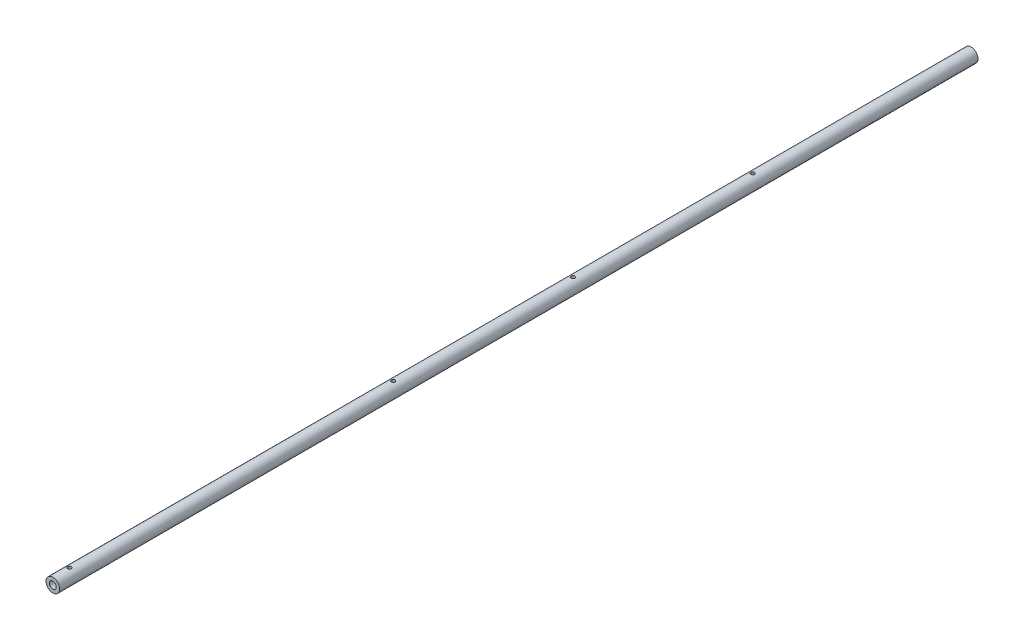
SolidWorks part; units mm, degrees
ref_plane "Front Plane" through (0, 0, 0) normal (0, 0, 1) x (1, 0, 0)
ref_plane "Top Plane" through (0, 0, 0) normal (0, 1, 0) x (1, 0, 0)
ref_plane "Right Plane" through (0, 0, 0) normal (1, 0, 0) x (0, 0, -1)
sketch "Sketch1" plane through (0, 0, 0) normal (0, 0, 1) x (1, 0, 0)
  circle A0 centre (0, 0) radius 3.9306
  circle A1 centre (0, 0) radius 7.8613
  dimension "D1" = 15.7226
  dimension "D2" = 7.8613
extrude "Rod" add sketch "Sketch1" along normal blind 1054.1 contours A0
sketch "Sketch3" plane through (0, 0, 0) normal (0, 1, 0) x (1, 0, 0)
  line L0 (0, -663.575) -> (0, -1028.7) construction
  line L1 (-7.8613, -1054.1) -> (7.8613, -1054.1) construction
  circle A0 centre (0, -250.825) radius 2.1082
  circle A4 centre (0, -457.2) radius 2.1082
  circle A8 centre (0, -663.575) radius 2.1082
  circle A9 centre (0, -1035.05) radius 2.1082
  point P8 (0, 0)
  dimension "D1" = 4.2164
  dimension "D6" = 4.2164
  dimension "D2" = 250.825
  dimension "D4" = 206.375
  dimension "D5" = 365.125
  dimension "D7" = 19.05
  dimension "D3" = 3
extrude "Holes" cut sketch "Sketch3" against normal through all both and the other way through all
ref_plane "Handle Location" through (0, 0, 1028.7) normal (0, 0, 1) x (1, 0, 0)
equation "\"L\"= 41.5"
equation "\"D1@Rod\" = \"L\""
equation "\"N\"= 3"
equation "\"D3@Sketch3\"=\"N\""
equation "\"S\"= 8.125"
equation "\"D4@Sketch3\"=\"S\""
equation "\"O\"= 9.875"
equation "\"D2@Sketch3\"=\"O\""
equation "\"H\"= 14.375"
equation "\"D5@Sketch3\"=\"H\""
